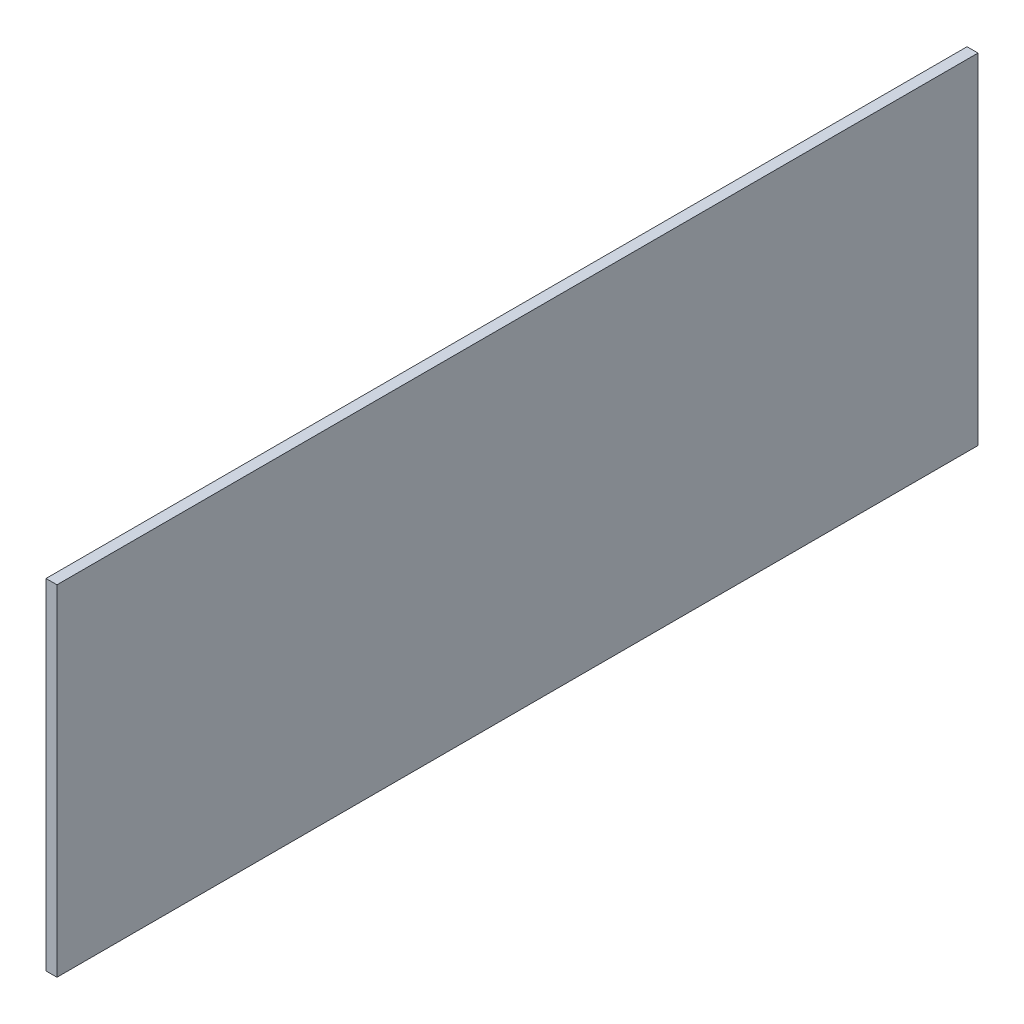
SolidWorks part; units mm, degrees
ref_plane "Front Plane" through (0, 0, 0) normal (0, 0, 1) x (1, 0, 0)
ref_plane "Top Plane" through (0, 0, 0) normal (0, 1, 0) x (1, 0, 0)
ref_plane "Right Plane" through (0, 0, 0) normal (1, 0, 0) x (0, 0, -1)
sketch "Sketch1" plane through (0, 0, 0) normal (1, 0, 0) x (0, 0, -1)
  line L1 (0, 0) -> (2100, 0)
  line L2 (0, 0) -> (0, 775)
  line L3 (0, 775) -> (2100, 775)
  line L4 (2100, 0) -> (2100, 775)
  dimension "D1" = 2100
  dimension "D2" = 775
extrude "Boss-Extrude1" add sketch "Sketch1" along normal blind 25
